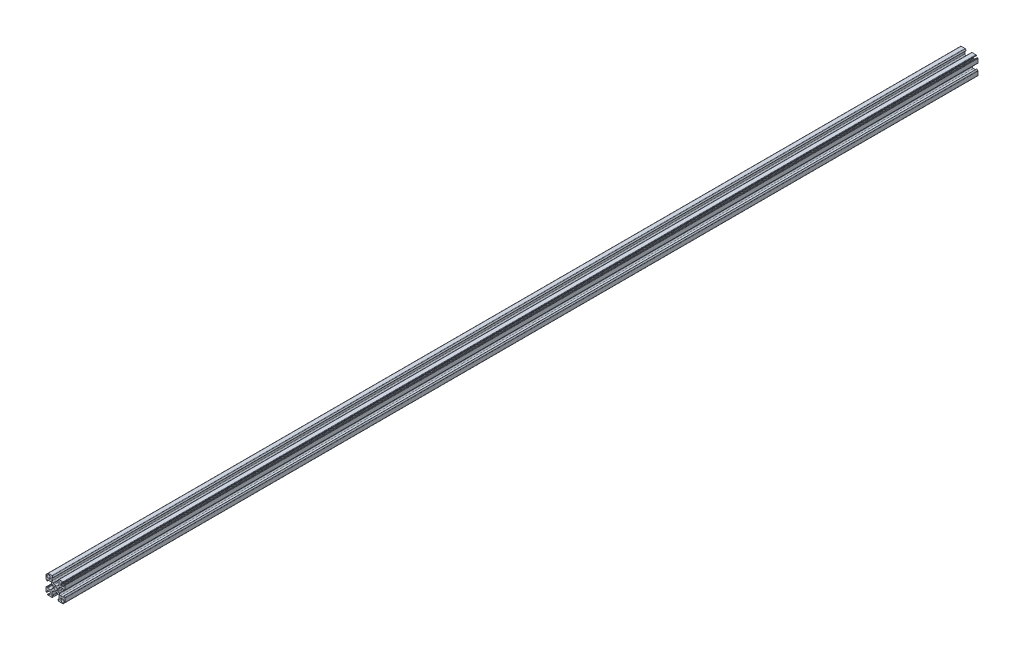
SolidWorks part; units mm, degrees
ref_plane "Front Plane" through (0, 0, 0) normal (0, 0, 1) x (1, 0, 0)
ref_plane "Top Plane" through (0, 0, 0) normal (0, 1, 0) x (1, 0, 0)
ref_plane "Right Plane" through (0, 0, 0) normal (1, 0, 0) x (0, 0, -1)
ref_plane "Plane1" through (0, 0, 0) normal (0, 0, -1) x (-1, 0, 0)
sketch "Sketch1" plane through (0, 0, 0) normal (0, 0, -1) x (-1, 0, 0)
  line L0 (-7.4885, 8.6199) -> (-6.9856, 8.117)
  line L1 (-6.9856, 7.4099) -> (-7.4099, 6.9856)
  line L2 (-8.117, 6.9856) -> (-8.6199, 7.4885)
  line L3 (-12.7, 9.7594) -> (-12.7, 4.7107)
  line L4 (-12.4803, 4.1803) -> (-11.2707, 2.9707)
  line L5 (-11.1, 3.0414) -> (-11.1, 4.325)
  line L6 (-10.6, 4.825) -> (-6.6, 4.825)
  line L7 (-5.1, 3.325) -> (-5.1, 3.15)
  line L8 (-3.6, 1.65) -> (-3.6, -1.65)
  line L9 (-5.1, -3.15) -> (-5.1, -3.325)
  line L10 (-6.6, -4.825) -> (-10.6, -4.825)
  line L11 (-11.1, -4.325) -> (-11.1, -3.0414)
  line L12 (-11.2707, -2.9707) -> (-12.4803, -4.1803)
  line L13 (-12.7, -4.7107) -> (-12.7, -9.7594)
  line L14 (-8.6199, -7.4885) -> (-8.117, -6.9856)
  line L15 (-7.4099, -6.9856) -> (-6.9856, -7.4099)
  line L16 (-6.9856, -8.117) -> (-7.4885, -8.6199)
  line L17 (-9.7594, -12.7) -> (-4.7107, -12.7)
  line L18 (-4.1803, -12.4803) -> (-2.9707, -11.2707)
  line L19 (-3.0414, -11.1) -> (-4.325, -11.1)
  line L20 (-4.825, -10.6) -> (-4.825, -6.6)
  line L21 (-3.325, -5.1) -> (-3.15, -5.1)
  line L22 (-1.65, -3.6) -> (1.65, -3.6)
  line L23 (3.15, -5.1) -> (3.325, -5.1)
  line L24 (4.825, -6.6) -> (4.825, -10.6)
  line L25 (4.325, -11.1) -> (3.0414, -11.1)
  line L26 (2.9707, -11.2707) -> (4.1803, -12.4803)
  line L27 (4.7107, -12.7) -> (9.7594, -12.7)
  line L28 (7.4885, -8.6199) -> (6.9856, -8.117)
  line L29 (6.9856, -7.4099) -> (7.4099, -6.9856)
  line L30 (8.117, -6.9856) -> (8.6199, -7.4885)
  line L31 (12.7, -9.7594) -> (12.7, -4.7107)
  line L32 (12.4803, -4.1803) -> (11.2707, -2.9707)
  line L33 (11.1, -3.0414) -> (11.1, -4.325)
  line L34 (10.6, -4.825) -> (6.6, -4.825)
  line L35 (5.1, -3.325) -> (5.1, -3.15)
  line L36 (3.6, -1.65) -> (3.6, 1.65)
  line L37 (5.1, 3.15) -> (5.1, 3.325)
  line L38 (6.6, 4.825) -> (10.6, 4.825)
  line L39 (11.1, 4.325) -> (11.1, 3.0414)
  line L40 (11.2707, 2.9707) -> (12.4803, 4.1803)
  line L41 (12.7, 4.7107) -> (12.7, 9.7594)
  line L42 (8.6199, 7.4885) -> (8.117, 6.9856)
  line L43 (7.4099, 6.9856) -> (6.9856, 7.4099)
  line L44 (6.9856, 8.117) -> (7.4885, 8.6199)
  line L45 (9.7594, 12.7) -> (4.7107, 12.7)
  line L46 (4.1803, 12.4803) -> (2.9707, 11.2707)
  line L47 (3.0414, 11.1) -> (4.325, 11.1)
  line L48 (4.825, 10.6) -> (4.825, 6.6)
  line L49 (3.325, 5.1) -> (3.15, 5.1)
  line L50 (1.65, 3.6) -> (-1.65, 3.6)
  line L51 (-3.15, 5.1) -> (-3.325, 5.1)
  line L52 (-4.825, 6.6) -> (-4.825, 10.6)
  line L53 (-4.325, 11.1) -> (-3.0414, 11.1)
  line L54 (-2.9707, 11.2707) -> (-4.1803, 12.4803)
  line L55 (-4.7107, 12.7) -> (-9.7594, 12.7)
  circle A0 centre (0, 0) radius 2.08
  arc A1 (-9.7594, 12.7) -> (-10.4266, 12.2927) centre (-9.7594, 11.95) ccw
  arc A2 (-10.4266, 12.2927) -> (-9.8933, 11.5721) centre (-9.9818, 12.0642) ccw
  arc A3 (-9.8933, 11.5721) -> (-7.5492, 8.8748) centre (-9.525, 9.525) cw
  arc A4 (-7.5492, 8.8748) -> (-7.4885, 8.6199) centre (-7.3118, 8.7967) ccw
  arc A5 (-6.9856, 8.117) -> (-6.9856, 7.4099) centre (-7.3392, 7.7635) cw
  arc A6 (-7.4099, 6.9856) -> (-8.117, 6.9856) centre (-7.7635, 7.3392) cw
  arc A7 (-8.6199, 7.4885) -> (-8.8748, 7.5492) centre (-8.7967, 7.3118) ccw
  arc A8 (-8.8748, 7.5492) -> (-11.5721, 9.8933) centre (-9.525, 9.525) cw
  arc A9 (-11.5721, 9.8933) -> (-12.2927, 10.4266) centre (-12.0642, 9.9818) ccw
  arc A10 (-12.2927, 10.4266) -> (-12.7, 9.7594) centre (-11.95, 9.7594) ccw
  arc A11 (-12.7, 4.7107) -> (-12.4803, 4.1803) centre (-11.95, 4.7107) ccw
  arc A12 (-11.2707, 2.9707) -> (-11.1, 3.0414) centre (-11.2, 3.0414) ccw
  arc A13 (-11.1, 4.325) -> (-10.6, 4.825) centre (-10.6, 4.325) cw
  arc A14 (-6.6, 4.825) -> (-5.1, 3.325) centre (-6.6, 3.325) cw
  arc A15 (-5.1, 3.15) -> (-4.6, 2.65) centre (-4.6, 3.15) ccw
  arc A16 (-4.6, 2.65) -> (-3.6, 1.65) centre (-4.6, 1.65) cw
  arc A17 (-3.6, -1.65) -> (-4.6, -2.65) centre (-4.6, -1.65) cw
  arc A18 (-4.6, -2.65) -> (-5.1, -3.15) centre (-4.6, -3.15) ccw
  arc A19 (-5.1, -3.325) -> (-6.6, -4.825) centre (-6.6, -3.325) cw
  arc A20 (-10.6, -4.825) -> (-11.1, -4.325) centre (-10.6, -4.325) cw
  arc A21 (-11.1, -3.0414) -> (-11.2707, -2.9707) centre (-11.2, -3.0414) ccw
  arc A22 (-12.4803, -4.1803) -> (-12.7, -4.7107) centre (-11.95, -4.7107) ccw
  arc A23 (-12.7, -9.7594) -> (-12.2927, -10.4266) centre (-11.95, -9.7594) ccw
  arc A24 (-12.2927, -10.4266) -> (-11.5721, -9.8933) centre (-12.0642, -9.9818) ccw
  arc A25 (-11.5721, -9.8933) -> (-8.8748, -7.5492) centre (-9.525, -9.525) cw
  arc A26 (-8.8748, -7.5492) -> (-8.6199, -7.4885) centre (-8.7967, -7.3118) ccw
  arc A27 (-8.117, -6.9856) -> (-7.4099, -6.9856) centre (-7.7635, -7.3392) cw
  arc A28 (-6.9856, -7.4099) -> (-6.9856, -8.117) centre (-7.3392, -7.7635) cw
  arc A29 (-7.4885, -8.6199) -> (-7.5492, -8.8748) centre (-7.3118, -8.7967) ccw
  arc A30 (-7.5492, -8.8748) -> (-9.8933, -11.5721) centre (-9.525, -9.525) cw
  arc A31 (-9.8933, -11.5721) -> (-10.4266, -12.2927) centre (-9.9818, -12.0642) ccw
  arc A32 (-10.4266, -12.2927) -> (-9.7594, -12.7) centre (-9.7594, -11.95) ccw
  arc A33 (-4.7107, -12.7) -> (-4.1803, -12.4803) centre (-4.7107, -11.95) ccw
  arc A34 (-2.9707, -11.2707) -> (-3.0414, -11.1) centre (-3.0414, -11.2) ccw
  arc A35 (-4.325, -11.1) -> (-4.825, -10.6) centre (-4.325, -10.6) cw
  arc A36 (-4.825, -6.6) -> (-3.325, -5.1) centre (-3.325, -6.6) cw
  arc A37 (-3.15, -5.1) -> (-2.65, -4.6) centre (-3.15, -4.6) ccw
  arc A38 (-2.65, -4.6) -> (-1.65, -3.6) centre (-1.65, -4.6) cw
  arc A39 (1.65, -3.6) -> (2.65, -4.6) centre (1.65, -4.6) cw
  arc A40 (2.65, -4.6) -> (3.15, -5.1) centre (3.15, -4.6) ccw
  arc A41 (3.325, -5.1) -> (4.825, -6.6) centre (3.325, -6.6) cw
  arc A42 (4.825, -10.6) -> (4.325, -11.1) centre (4.325, -10.6) cw
  arc A43 (3.0414, -11.1) -> (2.9707, -11.2707) centre (3.0414, -11.2) ccw
  arc A44 (4.1803, -12.4803) -> (4.7107, -12.7) centre (4.7107, -11.95) ccw
  arc A45 (9.7594, -12.7) -> (10.4266, -12.2927) centre (9.7594, -11.95) ccw
  arc A46 (10.4266, -12.2927) -> (9.8933, -11.5721) centre (9.9818, -12.0642) ccw
  arc A47 (9.8933, -11.5721) -> (7.5492, -8.8748) centre (9.525, -9.525) cw
  arc A48 (7.5492, -8.8748) -> (7.4885, -8.6199) centre (7.3118, -8.7967) ccw
  arc A49 (6.9856, -8.117) -> (6.9856, -7.4099) centre (7.3392, -7.7635) cw
  arc A50 (7.4099, -6.9856) -> (8.117, -6.9856) centre (7.7635, -7.3392) cw
  arc A51 (8.6199, -7.4885) -> (8.8748, -7.5492) centre (8.7967, -7.3118) ccw
  arc A52 (8.8748, -7.5492) -> (11.5721, -9.8933) centre (9.525, -9.525) cw
  arc A53 (11.5721, -9.8933) -> (12.2927, -10.4266) centre (12.0642, -9.9818) ccw
  arc A54 (12.2927, -10.4266) -> (12.7, -9.7594) centre (11.95, -9.7594) ccw
  arc A55 (12.7, -4.7107) -> (12.4803, -4.1803) centre (11.95, -4.7107) ccw
  arc A56 (11.2707, -2.9707) -> (11.1, -3.0414) centre (11.2, -3.0414) ccw
  arc A57 (11.1, -4.325) -> (10.6, -4.825) centre (10.6, -4.325) cw
  arc A58 (6.6, -4.825) -> (5.1, -3.325) centre (6.6, -3.325) cw
  arc A59 (5.1, -3.15) -> (4.6, -2.65) centre (4.6, -3.15) ccw
  arc A60 (4.6, -2.65) -> (3.6, -1.65) centre (4.6, -1.65) cw
  arc A61 (3.6, 1.65) -> (4.6, 2.65) centre (4.6, 1.65) cw
  arc A62 (4.6, 2.65) -> (5.1, 3.15) centre (4.6, 3.15) ccw
  arc A63 (5.1, 3.325) -> (6.6, 4.825) centre (6.6, 3.325) cw
  arc A64 (10.6, 4.825) -> (11.1, 4.325) centre (10.6, 4.325) cw
  arc A65 (11.1, 3.0414) -> (11.2707, 2.9707) centre (11.2, 3.0414) ccw
  arc A66 (12.4803, 4.1803) -> (12.7, 4.7107) centre (11.95, 4.7107) ccw
  arc A67 (12.7, 9.7594) -> (12.2927, 10.4266) centre (11.95, 9.7594) ccw
  arc A68 (12.2927, 10.4266) -> (11.5721, 9.8933) centre (12.0642, 9.9818) ccw
  arc A69 (11.5721, 9.8933) -> (8.8748, 7.5492) centre (9.525, 9.525) cw
  arc A70 (8.8748, 7.5492) -> (8.6199, 7.4885) centre (8.7967, 7.3118) ccw
  arc A71 (8.117, 6.9856) -> (7.4099, 6.9856) centre (7.7635, 7.3392) cw
  arc A72 (6.9856, 7.4099) -> (6.9856, 8.117) centre (7.3392, 7.7635) cw
  arc A73 (7.4885, 8.6199) -> (7.5492, 8.8748) centre (7.3118, 8.7967) ccw
  arc A74 (7.5492, 8.8748) -> (9.8933, 11.5721) centre (9.525, 9.525) cw
  arc A75 (9.8933, 11.5721) -> (10.4266, 12.2927) centre (9.9818, 12.0642) ccw
  arc A76 (10.4266, 12.2927) -> (9.7594, 12.7) centre (9.7594, 11.95) ccw
  arc A77 (4.7107, 12.7) -> (4.1803, 12.4803) centre (4.7107, 11.95) ccw
  arc A78 (2.9707, 11.2707) -> (3.0414, 11.1) centre (3.0414, 11.2) ccw
  arc A79 (4.325, 11.1) -> (4.825, 10.6) centre (4.325, 10.6) cw
  arc A80 (4.825, 6.6) -> (3.325, 5.1) centre (3.325, 6.6) cw
  arc A81 (3.15, 5.1) -> (2.65, 4.6) centre (3.15, 4.6) ccw
  arc A82 (2.65, 4.6) -> (1.65, 3.6) centre (1.65, 4.6) cw
  arc A83 (-1.65, 3.6) -> (-2.65, 4.6) centre (-1.65, 4.6) cw
  arc A84 (-2.65, 4.6) -> (-3.15, 5.1) centre (-3.15, 4.6) ccw
  arc A85 (-3.325, 5.1) -> (-4.825, 6.6) centre (-3.325, 6.6) cw
  arc A86 (-4.825, 10.6) -> (-4.325, 11.1) centre (-4.325, 10.6) cw
  arc A87 (-3.0414, 11.1) -> (-2.9707, 11.2707) centre (-3.0414, 11.2) ccw
  arc A88 (-4.1803, 12.4803) -> (-4.7107, 12.7) centre (-4.7107, 11.95) ccw
extrude "Boss-Extrude1" add sketch "Sketch1" against normal blind 1219.2
sketch "Sketch2" plane through (-12.7, 0, 0) normal (-1, 0, 0) x (0, 0, 1)
  line L0 (1219.2, -9.7594) -> (1219.2, -4.7107) construction
  line L1 (381, 112.119) -> (1219.2, 112.119)
  line L2 (381, 112.119) -> (381, -65.05)
  line L3 (381, -65.05) -> (1219.2, -65.05)
  line L4 (1219.2, 112.119) -> (1219.2, -65.05)
  dimension "D1" = 381
  dimension "D2" = 0
extrude "Cut-Extrude1" [suppressed] cut sketch "Sketch2" against normal through all
